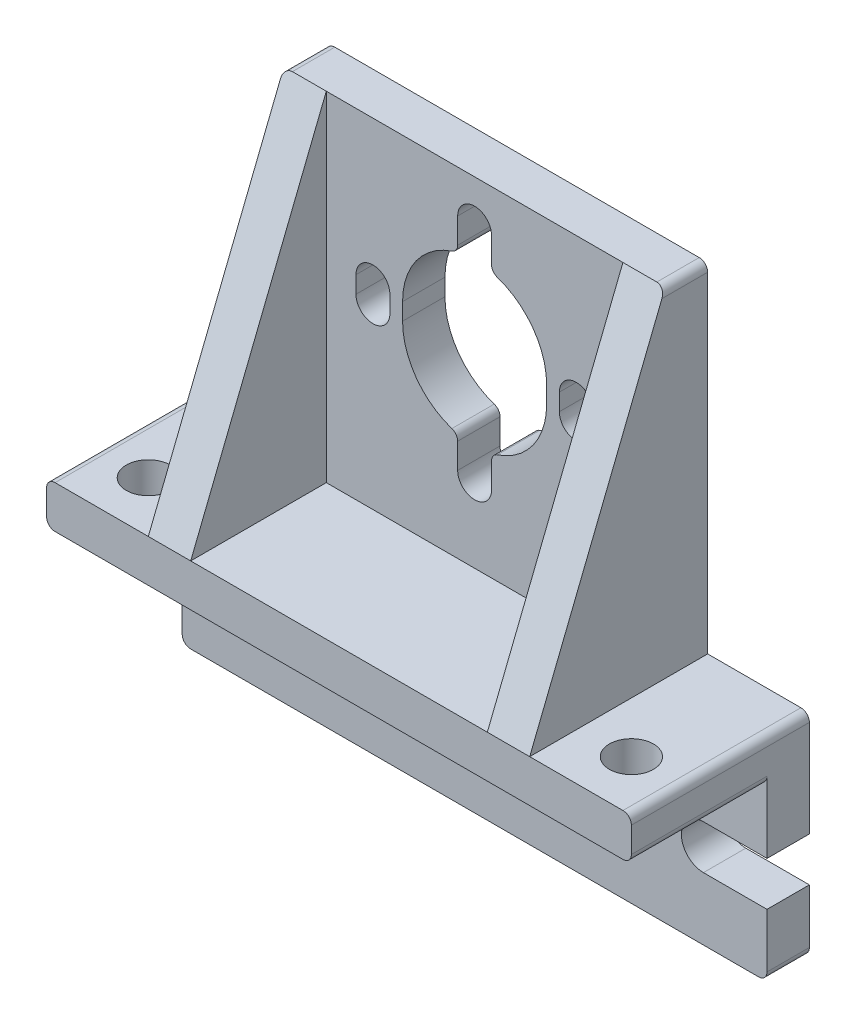
SolidWorks part; units mm, degrees
ref_plane "XY" through (0, 0, 0) normal (0, 0, 1) x (1, 0, 0)
ref_plane "XZ" through (0, 0, 0) normal (0, 1, 0) x (1, 0, 0)
ref_plane "YZ" through (0, 0, 0) normal (1, 0, 0) x (0, 0, -1)
sketch "Sketch1" plane through (0, 0, 0) normal (0, 0, 1) x (1, 0, 0)
  line L0 (0, 30.5) -> (0, -36.5314) construction
  line L1 (-34.5, -32.5) -> (34.5, -32.5)
  line L2 (-34.5, -32.5) -> (-34.5, -25.1)
  line L3 (-34.5, 32.5) -> (-22.5, 32.5) construction
  line L4 (34.5, -32.5) -> (34.5, -25.1)
  line L5 (-34.5, -32.5) -> (34.5, 32.5) construction
  line L6 (-34.5, 32.5) -> (34.5, -32.5) construction
  line L7 (-22.5, 32.5) -> (-22.5, -7.5)
  line L8 (-22.5, -7.5) -> (-34.5, -7.5)
  line L9 (22.5, 32.5) -> (22.5, -7.5)
  line L10 (22.5, -7.5) -> (34.5, -7.5)
  line L11 (-22.5, 32.5) -> (22.5, 32.5)
  line L12 (22.5, 32.5) -> (34.5, 32.5) construction
  line L13 (34.5, -7.5) -> (34.5, 32.5) construction
  line L14 (-34.5, -7.5) -> (-34.5, 32.5) construction
  line L15 (-27, -19.9) -> (-34.5, -19.9)
  line L16 (-27, -25.1) -> (-34.5, -25.1)
  line L17 (0, 27.5) -> (0, 1.5) construction
  line L18 (2, 27.5) -> (2, 1.5)
  line L19 (-2, 27.5) -> (-2, 1.5)
  line L20 (0, 15.5) -> (0, 13.5) construction
  line L21 (8.5, 15.5) -> (8.5, 13.5)
  line L22 (-8.5, 15.5) -> (-8.5, 13.5)
  line L23 (-12, 15.5) -> (-12, 13.5) construction
  line L24 (-10, 15.5) -> (-10, 13.5)
  line L25 (-14, 15.5) -> (-14, 13.5)
  line L26 (-34.5, -19.9) -> (-34.5, -7.5)
  line L27 (-34.5, -25.1) -> (-34.5, -19.9) construction
  line L28 (27, -25.1) -> (34.5, -25.1)
  line L29 (27, -19.9) -> (34.5, -19.9)
  line L30 (34.5, -19.9) -> (34.5, -7.5)
  line L31 (34.5, -25.1) -> (34.5, -19.9) construction
  line L32 (12, 15.5) -> (12, 13.5) construction
  line L33 (10, 15.5) -> (10, 13.5)
  line L34 (14, 15.5) -> (14, 13.5)
  arc A0 (-27, -25.1) -> (-27, -19.9) centre (-27, -22.5) ccw
  arc A1 (2, 27.5) -> (-2, 27.5) centre (0, 27.5) ccw
  arc A2 (-2, 1.5) -> (2, 1.5) centre (0, 1.5) ccw
  arc A3 (8.5, 15.5) -> (-8.5, 15.5) centre (0, 15.5) ccw
  arc A4 (-8.5, 13.5) -> (8.5, 13.5) centre (0, 13.5) ccw
  arc A5 (-10, 15.5) -> (-14, 15.5) centre (-12, 15.5) ccw
  arc A6 (-14, 13.5) -> (-10, 13.5) centre (-12, 13.5) ccw
  arc A7 (27, -25.1) -> (27, -19.9) centre (27, -22.5) cw
  arc A8 (10, 15.5) -> (14, 15.5) centre (12, 15.5) cw
  arc A9 (14, 13.5) -> (10, 13.5) centre (12, 13.5) cw
  point P0 (0, 0)
  point P22 (0, 14.5)
  point P27 (0, 14.5)
  point P34 (-12, 14.5)
  point P47 (12, 14.5)
  dimension "D5" = 5.2
  dimension "D10" = 2
  dimension "D14" = 2
  dimension "D1" = 69
  dimension "D2" = 65
  dimension "D3" = 40
  dimension "D4" = 12
  dimension "D6" = 22.5
  dimension "D7" = 27
  dimension "D8" = 14.5
  dimension "D9" = 26
  dimension "D11" = 2
  dimension "D12" = 17
  dimension "D13" = 2
  dimension "D15" = 12
extrude "Boss-Extrude1" add sketch "Sketch1" along normal blind 5 contours L28 A7 L29 L30 L10 L9 L11 L7 L8 L26 L15 A0 L16 L2 L1 L4 A6 L25 A5 L24 A4 L22 A3 L19 A1 L18 L21 A2 L34 A9 L33 A8
sketch "Sketch2" plane through (0, 0, 5) normal (0, 0, 1) x (1, 0, 0)
  line L0 (-22.5, 32.5) -> (-17.5, 32.5)
  line L1 (-22.5, 32.5) -> (22.5, 32.5) construction
  line L2 (-17.5, 32.5) -> (-17.5, -7.5)
  line L3 (-17.5, -7.5) -> (17.5, -7.5)
  line L4 (17.5, -7.5) -> (17.5, 32.5)
  line L5 (17.5, 32.5) -> (22.5, 32.5)
  line L6 (22.5, 32.5) -> (22.5, -7.5)
  line L7 (22.5, -7.5) -> (34.5, -7.5)
  line L8 (34.5, -7.5) -> (34.5, -12.5)
  line L9 (34.5, -19.9) -> (34.5, -7.5) construction
  line L10 (34.5, -12.5) -> (-34.5, -12.5)
  line L11 (-34.5, -19.9) -> (-34.5, -7.5) construction
  line L12 (-34.5, -12.5) -> (-34.5, -7.5)
  line L13 (-34.5, -7.5) -> (-22.5, -7.5)
  line L14 (-22.5, -7.5) -> (-22.5, 32.5)
  dimension "D1" = 5
  dimension "D2" = 5
  dimension "D3" = 5
extrude "Boss-Extrude2" add sketch "Sketch2" along normal blind 16
sketch "Sketch3" plane through (22.5, 0, 0) normal (1, 0, 0) x (0, 0, -1)
  line L0 (-21, -7.5) -> (-21, 32.5)
  line L1 (-21, 32.5) -> (-5, 32.5)
  line L2 (-21, 32.5) -> (0, 32.5) construction
  line L3 (-5, 32.5) -> (-21, -7.5)
  dimension "D1" = 16
extrude "Cut-Extrude1" cut sketch "Sketch3" against normal through all
sketch "Sketch4" plane through (0, -12.5, 0) normal (0, -1, 0) x (1, 0, 0)
  line L4 (0, 31.8901) -> (0, -11.7511) construction
  circle A0 centre (-28.5, 15) radius 2.6
  circle A1 centre (28.5, 15) radius 2.6
  dimension "D1" = 28.5
  dimension "D3" = 5.2
  dimension "D2" = 15
extrude "Cut-Extrude2" cut sketch "Sketch4" against normal blind 16
fillet "Fillet1" radius 1 8 edges at (-22.5, 32.5, 2.5) (22.5, 32.5, 2.5) (34.5, -7.5, 10.5) (34.5, -12.5, 13) (34.5, -32.5, 2.5) (-34.5, -7.5, 10.5) (-34.5, -12.5, 13) (-34.5, -32.5, 2.5)
fillet "Fillet2" radius 1 4 edges at (2, 23.7614, 2.5) (-2, 23.7614, 2.5) (-2, 5.2386, 2.5) (2, 5.2386, 2.5)
